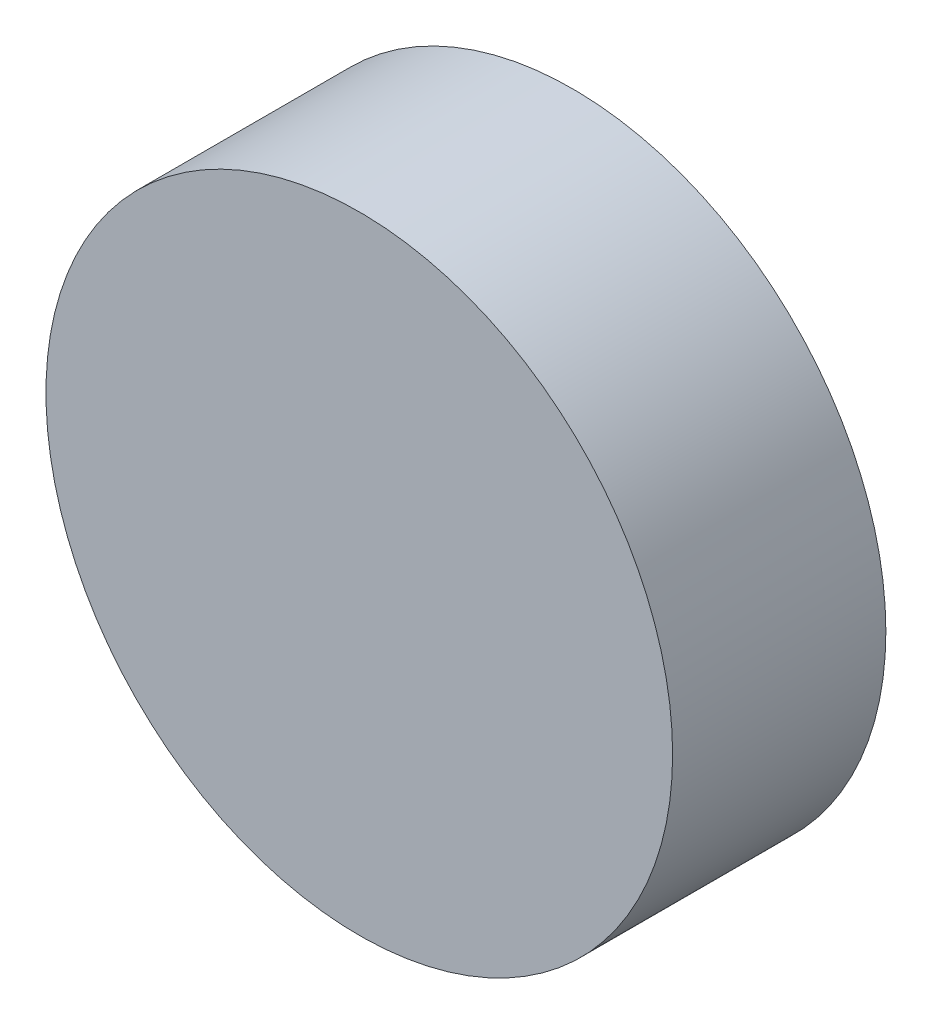
SolidWorks part; units mm, degrees
ref_plane "Front Plane" through (0, 0, 0) normal (0, 0, 1) x (1, 0, 0)
ref_plane "Top Plane" through (0, 0, 0) normal (0, 1, 0) x (1, 0, 0)
ref_plane "Right Plane" through (0, 0, 0) normal (1, 0, 0) x (0, 0, -1)
sketch "CurveSketch" plane through (0, 0, 0) normal (0, 0, 1) x (1, 0, 0)
  circle A0 centre (-3.719, 5.173) radius 17.237
  dimension "D1" = 17.237
extrude "CurveBoss" add sketch "CurveSketch" along normal blind 11.731
